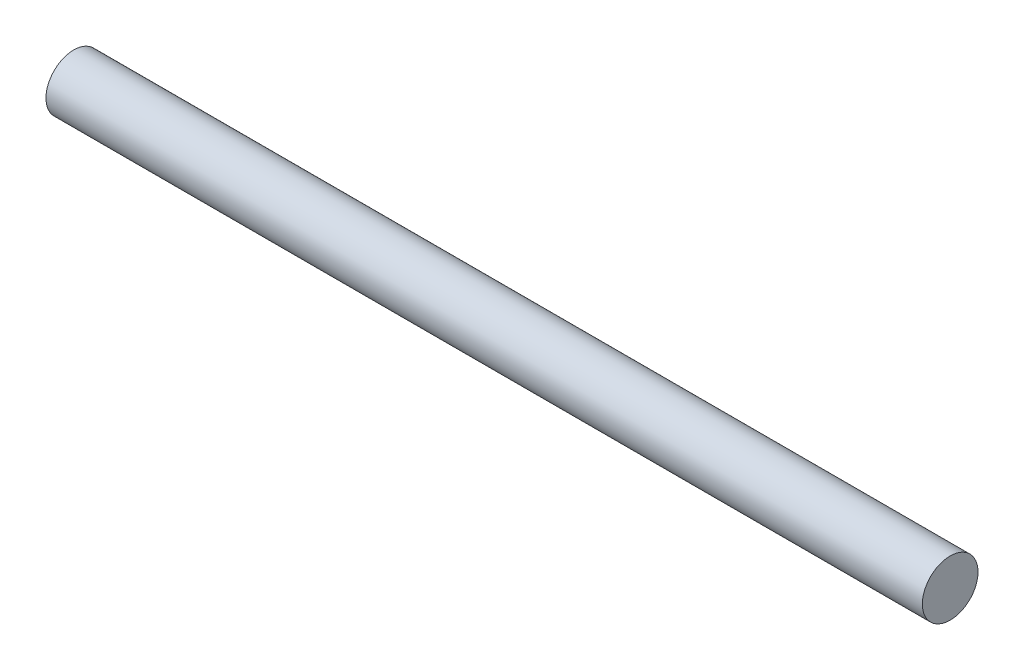
SolidWorks part; units mm, degrees
material "Cast Alloy Steel"
ref_plane "Front Plane" through (0, 0, 0) normal (0, 0, 1) x (1, 0, 0)
ref_plane "Top Plane" through (0, 0, 0) normal (0, 1, 0) x (1, 0, 0)
ref_plane "Right Plane" through (0, 0, 0) normal (1, 0, 0) x (0, 0, -1)
sketch "Sketch1" plane through (0, 0, 0) normal (1, 0, 0) x (0, 0, -1)
  circle A0 centre (0, 0) radius 4.7625
  dimension "D1" = 9.525
extrude "Boss-Extrude1" add sketch "Sketch1" along normal mid plane 150
